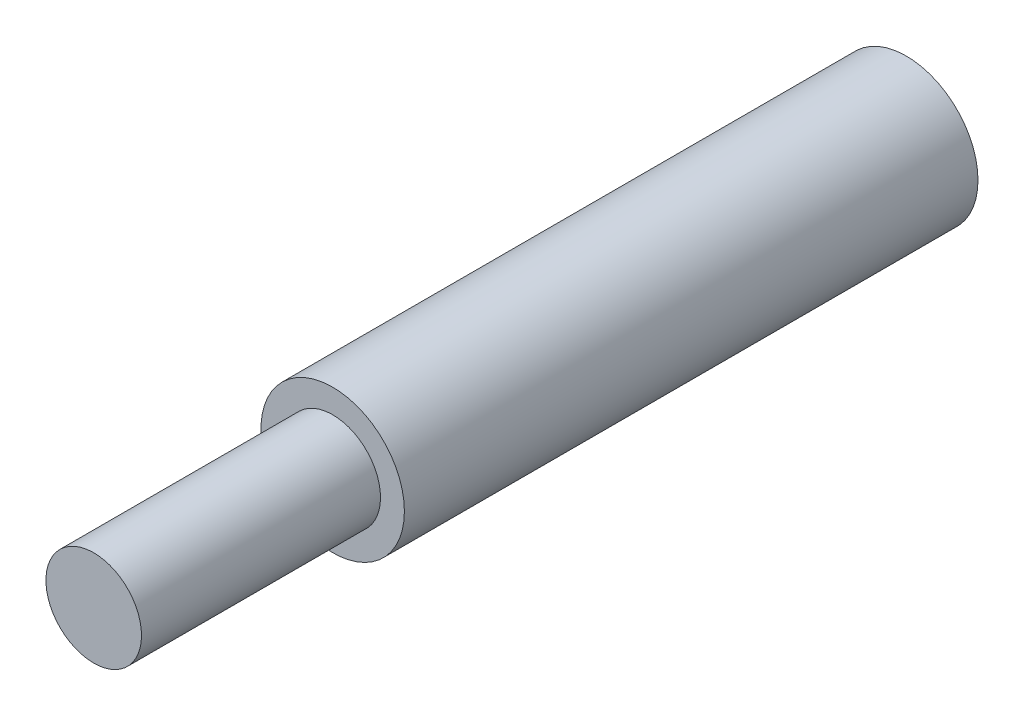
SolidWorks part; units mm, degrees
material "AISI 4340 Steel, normalized"
ref_plane "Front Plane" through (0, 0, 0) normal (0, 0, 1) x (1, 0, 0)
ref_plane "Top Plane" through (0, 0, 0) normal (0, 1, 0) x (1, 0, 0)
ref_plane "Right Plane" through (0, 0, 0) normal (1, 0, 0) x (0, 0, -1)
sketch "Sketch1" plane through (0, 0, 0) normal (0, 0, 1) x (1, 0, 0)
  circle A0 centre (0, 0) radius 3
extrude "Smooth_Stop_Shank_D6_L24" add sketch "Sketch1" along normal blind 24 from offset 24
sketch "Sketch2" plane through (0, 0, 0) normal (0, 0, 1) x (1, 0, 0)
  circle A0 centre (0, 0) radius 2
extrude "M4x0p7_Thread_Envelope_L10" add sketch "Sketch2" along normal blind 10
